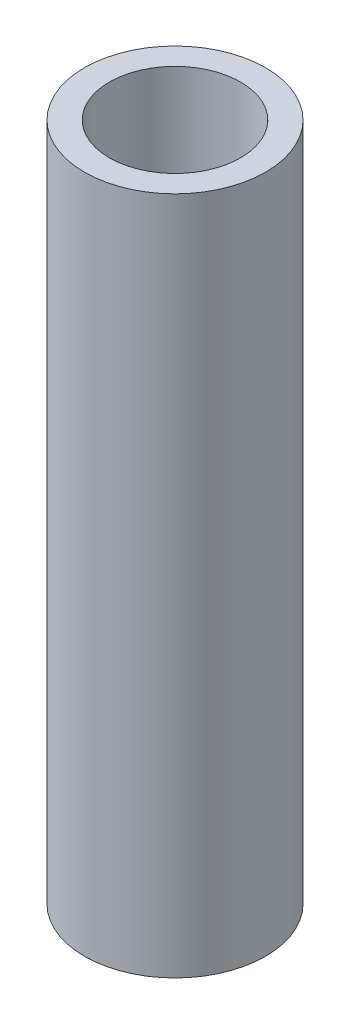
SolidWorks part; units mm, degrees
material "PLA плотность"
ref_plane "Спереди" through (0, 0, 0) normal (0, 0, 1) x (1, 0, 0)
ref_plane "Сверху" through (0, 0, 0) normal (0, 1, 0) x (1, 0, 0)
ref_plane "Справа" through (0, 0, 0) normal (1, 0, 0) x (0, 0, -1)
sketch "Эскиз1" plane through (0, 0, 0) normal (0, 1, 0) x (1, 0, 0)
  circle A0 centre (0, 0) radius 8
  circle A1 centre (0, 0) radius 5.8
  dimension "D1" = 16
  dimension "D2" = 2.2
extrude "Бобышка-Вытянуть1" add sketch "Эскиз1" along normal blind 60
